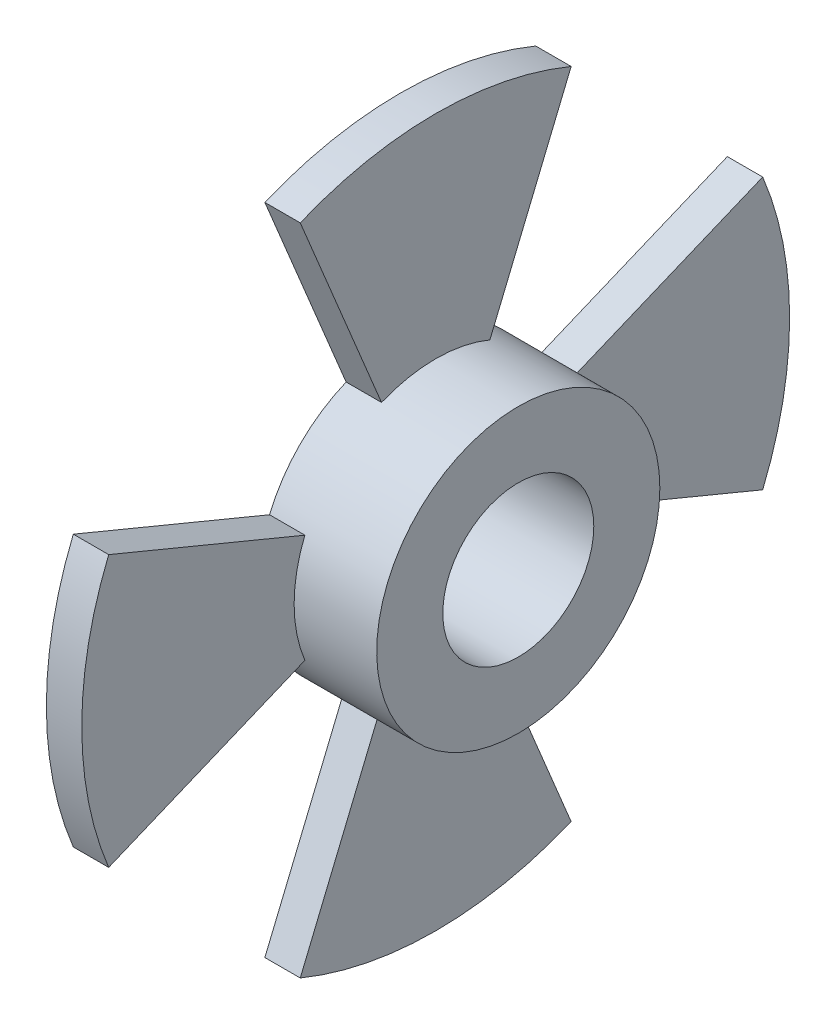
SolidWorks part; units mm, degrees
ref_plane "Alzado" through (0, 0, 0) normal (0, 0, 1) x (1, 0, 0)
ref_plane "Planta" through (0, 0, 0) normal (0, 1, 0) x (1, 0, 0)
ref_plane "Vista lateral" through (0, 0, 0) normal (1, 0, 0) x (0, 0, -1)
sketch "Croquis1" plane through (0, 0, 0) normal (1, 0, 0) x (0, 0, -1)
  line L0 (0, -387.8597) -> (0, 19005.1261) construction
  line L1 (-387.8597, 0) -> (19005.1261, 0) construction
  line L2 (0, 6) -> (0, 15)
  line L3 (5.7403, 13.8582) -> (2.2961, 5.5433)
  line L4 (4.2426, 4.2426) -> (10.6066, 10.6066)
  line L5 (13.8582, 5.7403) -> (5.5433, 2.2961)
  line L6 (6, 0) -> (15, 0)
  line L7 (13.8582, -5.7403) -> (5.5433, -2.2961)
  line L8 (4.2426, -4.2426) -> (10.6066, -10.6066)
  line L9 (5.7403, -13.8582) -> (2.2961, -5.5433)
  line L10 (0, -6) -> (0, -15)
  line L11 (-5.7403, -13.8582) -> (-2.2961, -5.5433)
  line L12 (-4.2426, -4.2426) -> (-10.6066, -10.6066)
  line L13 (-13.8582, -5.7403) -> (-5.5433, -2.2961)
  line L14 (-6, 0) -> (-15, 0)
  line L15 (-13.8582, 5.7403) -> (-5.5433, 2.2961)
  line L16 (-4.2426, 4.2426) -> (-10.6066, 10.6066)
  line L17 (-5.7403, 13.8582) -> (-2.2961, 5.5433)
  arc A0 (5.7403, 13.8582) -> (0, 15) centre (0, 0) ccw
  arc A1 (-4.2426, 4.2426) -> (-5.5433, 2.2961) centre (0, 0) ccw
  arc A2 (13.8582, 5.7403) -> (10.6066, 10.6066) centre (0, 0) ccw
  arc A3 (13.8582, -5.7403) -> (15, 0) centre (0, 0) ccw
  arc A4 (5.7403, -13.8582) -> (10.6066, -10.6066) centre (0, 0) ccw
  arc A5 (-5.7403, -13.8582) -> (0, -15) centre (0, 0) ccw
  arc A6 (-13.8582, -5.7403) -> (-10.6066, -10.6066) centre (0, 0) ccw
  arc A7 (-13.8582, 5.7403) -> (-15, 0) centre (0, 0) ccw
  arc A8 (-5.7403, 13.8582) -> (-10.6066, 10.6066) centre (0, 0) ccw
  arc A9 (0, 6) -> (-2.2961, 5.5433) centre (0, 0) ccw
  arc A10 (4.2426, 4.2426) -> (2.2961, 5.5433) centre (0, 0) ccw
  arc A11 (6, 0) -> (5.5433, 2.2961) centre (0, 0) ccw
  arc A12 (4.2426, -4.2426) -> (5.5433, -2.2961) centre (0, 0) ccw
  arc A13 (0, -6) -> (2.2961, -5.5433) centre (0, 0) ccw
  arc A14 (-4.2426, -4.2426) -> (-2.2961, -5.5433) centre (0, 0) ccw
  arc A15 (-6, 0) -> (-5.5433, -2.2961) centre (0, 0) ccw
  circle A16 centre (0, 0) radius 3.2
  circle A17 centre (0, 0) radius 15
  circle A18 centre (0, 0) radius 6
  point P42 (0, 0)
  dimension "D1" = 30
  dimension "D2" = 12
  dimension "D5" = 6.4
  dimension "D3" = 22.5
  dimension "D4" = 8
extrude "Saliente-Extruir1" add sketch "Croquis1" along normal mid plane 1.5 contours L2 A17 L17 A9 | A18 L3 A0 L2 | L6 A17 L5 A11 | A18 L7 A3 L6 | L10 A17 L9 A13 | A18 L11 A5 L10 | L14 A17 L13 A15 | A18 L15 A7 L14 | A11 A18 A10 A9 A1 A15 A14 A13 A12 A16
sketch "Croquis2" plane through (0.75, 0, 0) normal (1, 0, 0) x (0, 0, -1)
  circle A1 centre (0, 0) radius 3.2
  circle A2 centre (0, 0) radius 6
  arc A4 (-2.2961, 5.5433) -> (-5.5433, 2.2961) centre (0, 0) ccw construction
  circle A5 centre (0, 0) radius 3.2 construction
extrude "Saliente-Extruir2" add sketch "Croquis2" along normal blind 3.5
equation "\"x\"= 30"
equation "\"D2@Croquis1\"=\"x\"/2.5"
